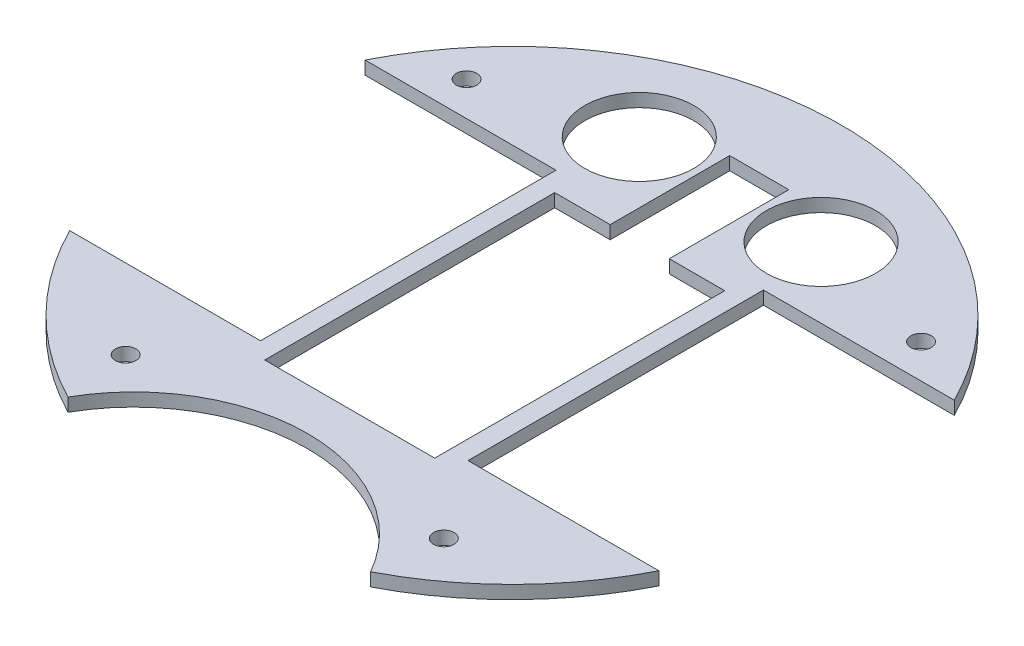
SolidWorks part; units mm, degrees
material "Acrylic (Medium-high impact)"
ref_plane "Front Plane" through (0, 0, 0) normal (0, 0, 1) x (1, 0, 0)
ref_plane "Top Plane" through (0, 0, 0) normal (0, 1, 0) x (1, 0, 0)
ref_plane "Right Plane" through (0, 0, 0) normal (1, 0, 0) x (0, 0, -1)
sketch "Sketch1" plane through (0, 0, 0) normal (0, 1, 0) x (1, 0, 0)
  line L0 (0, -83.2398) -> (-33.2911, -64.4046) construction
  line L1 (0, -83.2398) -> (0, 0) construction
  arc A0 (33.2911, -64.4046) -> (-33.2911, -64.4046) centre (0, 0) ccw
  arc A1 (33.2911, -64.4046) -> (-33.2911, -64.4046) centre (0, -83.2398) ccw
  dimension "D1" = 145
  dimension "D2" = 76.5
  dimension "D3" = 60.5
extrude "Boss-Extrude1" add sketch "Sketch1" along normal blind 2.9
sketch "solenoid placement" plane through (0, 2.9, 0) normal (0, 1, 0) x (1, 0, 0)
  line L4 (-18.7, -35.7) -> (18.7, -35.7)
  line L5 (18.7, -35.7) -> (18.7, 28.1)
  line L6 (18.7, 28.1) -> (-18.7, 28.1)
  line L7 (-18.7, 28.1) -> (-18.7, -35.7)
  line L8 (-18.7, -35.7) -> (18.7, -35.7)
  line L9 (18.7, -35.7) -> (18.7, 28.1)
  line L10 (18.7, 28.1) -> (-18.7, 28.1)
  line L11 (-18.7, 28.1) -> (-18.7, -35.7)
  circle A1 centre (0, 0) radius 72.5 construction
  arc A2 (33.2911, -64.4046) -> (-33.2911, -64.4046) centre (0, 0) ccw construction
  dimension "D1" = 0
extrude "Cut-Extrude1" cut sketch "solenoid placement" against normal through all
sketch "Sketch3" plane through (0, 2.9, 0) normal (0, 1, 0) x (1, 0, 0)
  line L4 (-34.63, -32.5) -> (-22.83, -32.5)
  line L5 (-22.83, -32.5) -> (-22.83, 32.5)
  line L6 (-22.83, 32.5) -> (-64.8074, 32.5)
  line L7 (-64.8074, -32.5) -> (-34.63, -32.5)
  line L8 (-34.63, -32.5) -> (-22.83, -32.5)
  line L9 (-22.83, -32.5) -> (-22.83, 32.5)
  line L10 (-22.83, 32.5) -> (-64.8074, 32.5)
  line L11 (-64.8074, -32.5) -> (-34.63, -32.5)
  line L12 (34.63, -32.5) -> (64.8074, -32.5)
  line L13 (64.8074, 32.5) -> (22.83, 32.5)
  line L14 (22.83, 32.5) -> (22.83, -32.5)
  line L15 (22.83, -32.5) -> (34.63, -32.5)
  line L16 (34.63, -32.5) -> (64.8074, -32.5)
  line L17 (64.8074, 32.5) -> (22.83, 32.5)
  line L18 (22.83, 32.5) -> (22.83, -32.5)
  line L19 (22.83, -32.5) -> (34.63, -32.5)
  arc A2 (-64.8074, 32.5) -> (-64.8074, -32.5) centre (0, 0) ccw
  arc A3 (-64.8074, 32.5) -> (-64.8074, -32.5) centre (0, 0) ccw
  arc A4 (64.8074, -32.5) -> (64.8074, 32.5) centre (0, 0) ccw
  arc A5 (64.8074, -32.5) -> (64.8074, 32.5) centre (0, 0) ccw
  dimension "D2" = 0
  dimension "D1" = 0
extrude "Cut-Extrude3" cut sketch "Sketch3" against normal through all
sketch "Sketch4" plane through (0, 2.9, 0) normal (0, 1, 0) x (1, 0, 0)
  line L0 (18.7, 28.1) -> (-18.7, 28.1) construction
  line L1 (-6.5, 28.1) -> (6.5, 28.1)
  line L2 (-6.5, 28.1) -> (-6.5, 54.4)
  line L3 (6.5, 54.4) -> (-6.5, 54.4) construction
  line L4 (6.5, 28.1) -> (6.5, 54.4)
  line L5 (6.5, 54.4) -> (-6.5, 54.4)
  point P6 (0, 28.1)
extrude "Cut-Extrude4" cut sketch "Sketch4" against normal through all
sketch "Sketch5" plane through (0, 2.9, 0) normal (0, 1, 0) x (1, 0, 0)
  circle A2 centre (-20, 48) radius 12
  circle A3 centre (-20, 48) radius 12
  circle A4 centre (20, 48) radius 12
  circle A21 centre (20, 48) radius 12
  dimension "D1" = 0
  dimension "D2" = 0
extrude "Cut-Extrude5" cut sketch "Sketch5" against normal through all
sketch "Sketch6" plane through (0, 2.9, 0) normal (0, 1, 0) x (1, 0, 0)
  circle A1 centre (35, -50) radius 2.25
  circle A2 centre (35, -50) radius 2.25
  circle A3 centre (-35, -50) radius 2.25
  circle A4 centre (-35, -50) radius 2.25
  circle A5 centre (-50, 40) radius 2.25
  circle A6 centre (-50, 40) radius 2.25
  circle A7 centre (50, 40) radius 2.25
  circle A8 centre (50, 40) radius 2.25
  dimension "D1" = 0
  dimension "D2" = 0
  dimension "D3" = 0
  dimension "D4" = 0
extrude "Cut-Extrude6" cut sketch "Sketch6" against normal through all
equation "\"smallPulleyTeeth\"= 15"
equation "\"largePulleyTeeth\"= 30"
equation "\"eighthThick\"= 2.9mm"
equation "\"sixteenthThick\"= 1.7mm"
equation "\"quarterThick\"=5.9mm"
equation "\"OD\"= 145mm"
equation "\"puckAngle\"= 60.5deg"
equation "\"D1@Sketch1\"=\"OD\""
equation "\"puckDiam\"= 76.5mm"
equation "\"D2@Sketch1\"=\"puckDiam\""
equation "\"D3@Sketch1\"=\"puckAngle\""
equation "\"D1@Boss-Extrude1\"=\"eighthThick\""
equation "\"axlePress\"= 5.9mm"
equation "\"press\"= 0.2mm"
equation "\"wheelClear\"= 0.3mm"
equation "\"10-32clear\"= 4.5mm"
equation "\"6-32clear\"= 3.3mm"
equation "\"8-32clear\"= 4.0mm"
equation "\"wheelHeight\"= 22mm"
equation "\"wheelWell\"= 65mm"
